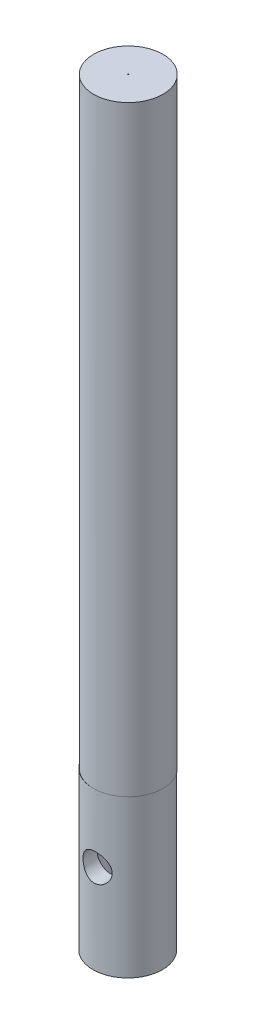
SolidWorks part; units mm, degrees
ref_plane "Front Plane" through (0, 0, 0) normal (0, 0, 1) x (1, 0, 0)
ref_plane "Top Plane" through (0, 0, 0) normal (0, 1, 0) x (1, 0, 0)
ref_plane "Right Plane" through (0, 0, 0) normal (1, 0, 0) x (0, 0, -1)
sketch "Sketch1" plane through (0, 0, 0) normal (0, 1, 0) x (1, 0, 0)
  line L0 (0, 0) -> (0, -2.5) construction
  line L1 (0, -0.06) -> (0, -2) construction
  line L2 (0, -2) -> (1.5, -2) construction
  line L3 (1.5, -2) -> (-1.5, -2)
  arc A0 (1.5, -2) -> (-1.5, -2) centre (0, 0) ccw
  circle A1 centre (0, 0) radius 3.75
  dimension "D1" = 7.5
  dimension "D3" = 2.5
  dimension "D2" = 3
extrude "Boss-Extrude1" add sketch "Sketch1" along normal blind 17
sketch "Sketch2" plane through (0, 17, 0) normal (0, 1, 0) x (1, 0, 0)
  circle A0 centre (0.0588, 0) radius 0.0588
  circle A1 centre (0.0588, 0) radius 3.75
  dimension "D1" = 7.5
extrude "Boss-Extrude2" add sketch "Sketch2" along normal blind 65
sketch "Sketch3" plane through (0, 0, 0) normal (0, 0, 1) x (1, 0, 0)
  line L0 (0.178, 0) -> (0.178, 10) construction
  circle A0 centre (0.178, 9.6747) radius 1.5
extrude "Cut-Extrude1" cut sketch "Sketch3" along normal up to next
